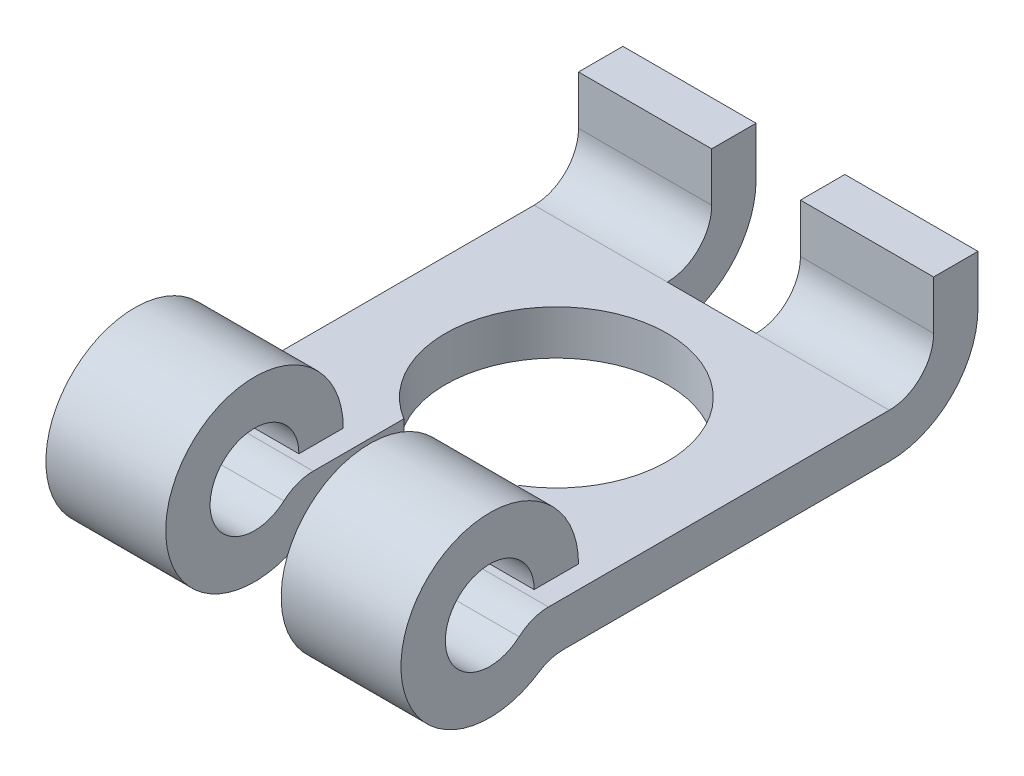
SolidWorks part; units mm, degrees
ref_plane "Front Plane" through (0, 0, 0) normal (0, 0, 1) x (1, 0, 0)
ref_plane "Top Plane" through (0, 0, 0) normal (0, 1, 0) x (1, 0, 0)
ref_plane "Right Plane" through (0, 0, 0) normal (1, 0, 0) x (0, 0, -1)
sketch "Sketch2" plane through (0, 0, 0) normal (1, 0, 0) x (0, 0, -1)
  line L0 (0, 15) -> (10, 15)
  line L1 (3.2288, 0) -> (100, 0)
  line L2 (10, 10) -> (20, 10)
  line L3 (-1.3397, 10) -> (90, 10)
  line L4 (100, 0) -> (100, 10)
  line L5 (100, 0) -> (90, 0)
  line L6 (100, 0) -> (100, 31)
  line L7 (100, 31) -> (90, 31)
  line L8 (90, 10) -> (90, 31)
  arc A0 (0, 15) -> (-1.3397, 10) centre (-10, 15) ccw
  arc A1 (10, 15) -> (3.2288, 0) centre (-10, 15) ccw
extrude "Boss-Extrude7" add sketch "Sketch2" along normal blind 80 contours L0 A1 L1 L4 L6 L7 L8 L3 L2 A0
fillet "Fillet1" radius 10 1 edges at (40, 10, -90)
fillet "Fillet2" radius 10 2 edges at (40, 0, -3.2288) (40, 10, 1.3397)
sketch "Sketch3" plane through (0, 0, 0) normal (0, 1, 0) x (1, 0, 0)
  line L0 (27, 10) -> (27, -31.663)
  line L1 (30, 80) -> (30, 108.9664)
  line L2 (27, -31.663) -> (53, -31.663)
  line L3 (0, 10) -> (27, 10)
  line L4 (80, 10) -> (53, 10)
  line L5 (27, 10) -> (27, 23.6458)
  line L6 (30, 80) -> (50, 80)
  line L7 (53, 10) -> (53, 23.6458)
  line L8 (53, -31.663) -> (53, 10)
  line L9 (80, 80) -> (0, 80) construction
  line L10 (30, 108.9664) -> (50, 108.9664)
  line L11 (50, 108.9664) -> (50, 80)
  arc A0 (53, 23.6458) -> (27, 23.6458) centre (40, 45) ccw
extrude "Cut-Extrude1" cut sketch "Sketch3" along normal mid plane 80 contours L7 A0 L5 L0 L2 L8 | L11 L10 L1 L6
fillet "Fillet4" radius 20 2 edges at (15, 0, -100) (65, 0, -100)
